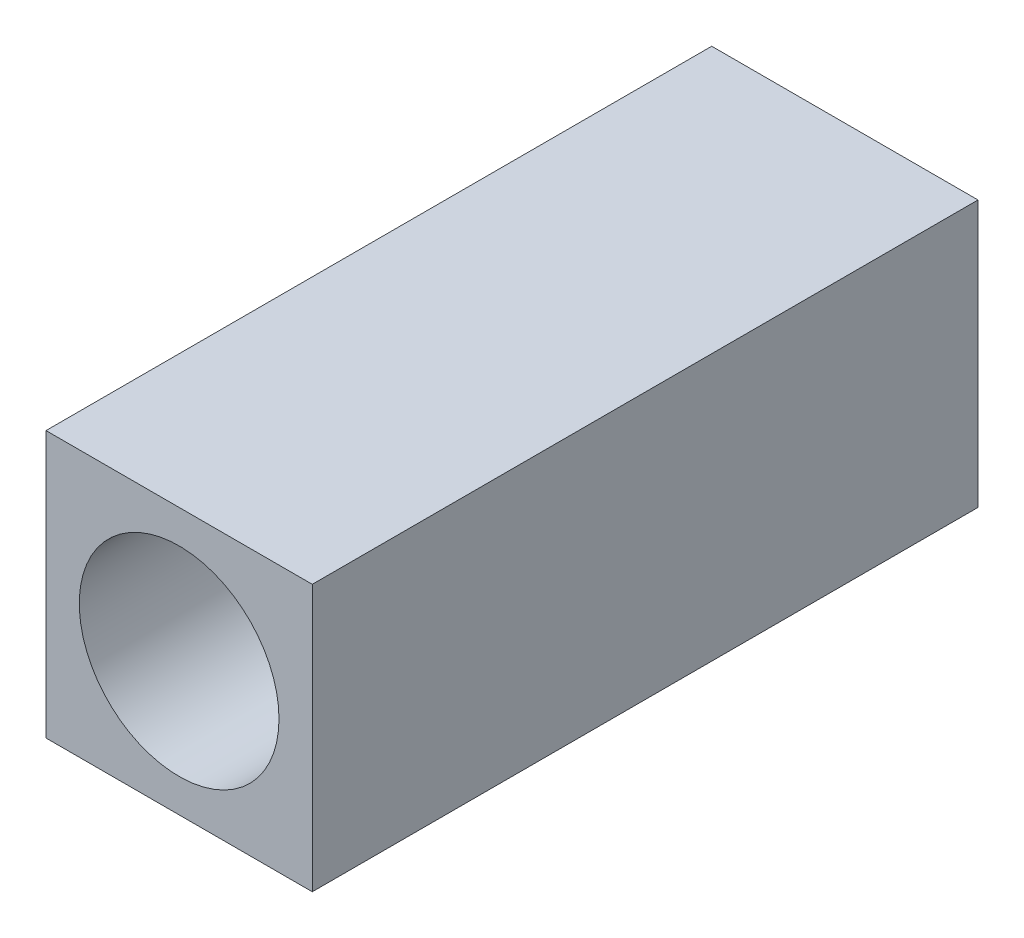
SolidWorks part; units mm, degrees
material "Custom Plastic"
ref_plane "Front Plane" through (0, 0, 0) normal (0, 0, 1) x (1, 0, 0)
ref_plane "Top Plane" through (0, 0, 0) normal (0, 1, 0) x (1, 0, 0)
ref_plane "Right Plane" through (0, 0, 0) normal (1, 0, 0) x (0, 0, -1)
other "Configuration Table"
sketch "Sketch1" plane through (0, 0, 0) normal (0, 0, 1) x (1, 0, 0)
  line L1 (-40, -40) -> (40, -40)
  line L2 (-40, -40) -> (-40, 40)
  line L3 (-40, 40) -> (40, 40)
  line L4 (40, -40) -> (40, 40)
  line L5 (-40, -40) -> (40, 40) construction
  line L6 (-40, 40) -> (40, -40) construction
  circle A0 centre (0, 0) radius 30
  dimension "D1" = 60
  dimension "D2" = 80
extrude "Boss-Extrude1" add sketch "Sketch1" along normal mid plane 200
